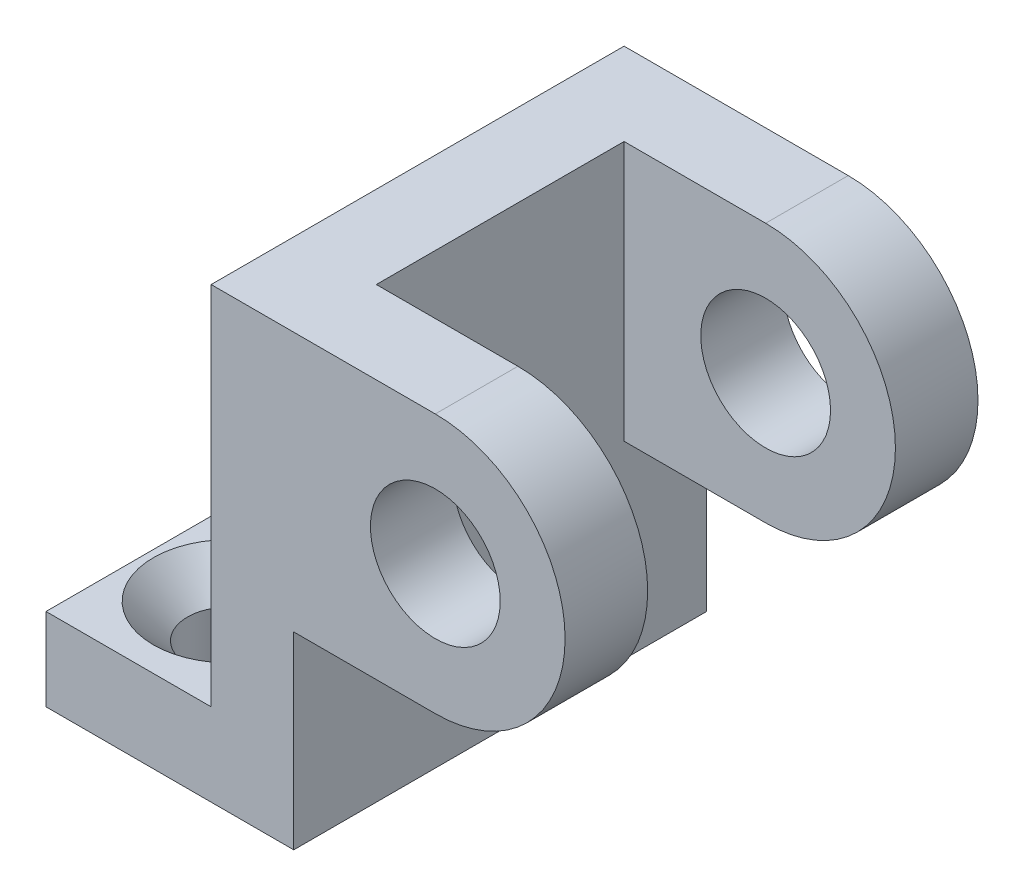
SolidWorks part; units mm, degrees
ref_plane "前视基准面" through (0, 0, 0) normal (0, 0, 1) x (1, 0, 0)
ref_plane "上视基准面" through (0, 0, 0) normal (0, 1, 0) x (1, 0, 0)
ref_plane "右视基准面" through (0, 0, 0) normal (1, 0, 0) x (0, 0, -1)
other "Configuration Table"
sketch "草图1" plane through (0, 0, 0) normal (0, 1, 0) x (1, 0, 0)
  line L1 (7, -17.5) -> (-7, -17.5)
  line L2 (7, -17.5) -> (7, 17.5)
  line L3 (7, 17.5) -> (-7, 17.5)
  line L4 (-7, -17.5) -> (-7, 17.5)
  line L5 (7, -17.5) -> (-7, 17.5) construction
  line L6 (7, 17.5) -> (-7, -17.5) construction
  point P0 (0, 0)
  dimension "D1" = 14
  dimension "D2" = 35
extrude "凸台-拉伸1" add sketch "草图1" along normal blind 7
ref_plane "基准面1" through (0, 7, 0) normal (0, 1, 0) x (1, 0, 0)
sketch "草图4" plane through (0, 7, 0) normal (0, 1, 0) x (1, 0, 0)
  line L0 (0, 0) -> (0, 19.8046) construction
  circle A0 centre (0, 9) radius 0.5
  circle A1 centre (0, -9) radius 0.5
  point P1 (0, 9)
  point P6 (0, -9)
  dimension "D1" = 1
  dimension "D2" = 1
  dimension "D3" = 9
  dimension "D4" = 9
hole_wizard "M6 内六角花形半沉头螺钉的锥形沉头孔1" positions "草图4" profile "草图5" countersink size "M6" standard "GB" end condition through all
sketch "草图5" plane through (0, 7, 9) normal (1, 0, 0) x (0, 0, 1)
  line L0 (0, 0) -> (0, 7)
  line L1 (0, 7) -> (3.5, 7)
  line L2 (3.5, 7) -> (3.5, 2.9)
  line L3 (3.5, 2.9) -> (6.4, 0)
  line L5 (6.4, 0) -> (0, 0)
  line L6 (-3.5, 2.9) -> (-6.4, 0) construction
  line L11 (0, -6.35) -> (0, 107.95) construction
  dimension "通孔孔直径" = 7
  dimension "通孔孔深度" = 7
  dimension "近端锥形沉头孔直径" = 12.8
  dimension "近端锥形沉头孔角度" = 90
sketch "草图6" plane through (0, 0, 0) normal (0, 1, 0) x (1, 0, 0)
  line L1 (7, 17.5) -> (14, 17.5)
  line L2 (7, 17.5) -> (7, -17.5)
  line L3 (7, -17.5) -> (14, -17.5)
  line L4 (14, 17.5) -> (14, -17.5)
  line L5 (7, 17.5) -> (14, -17.5) construction
  line L6 (7, -17.5) -> (14, 17.5) construction
  point P0 (10.5, 0)
  dimension "D1" = 35
  dimension "D2" = 7
  dimension "D3" = 10.5
extrude "凸台-拉伸2" add sketch "草图6" along normal blind 38
ref_plane "基准面2" through (0, 0, 17.5) normal (0, 0, 1) x (1, 0, 0)
sketch "草图7" plane through (0, 0, 17.5) normal (0, 0, 1) x (1, 0, 0)
  line L0 (14, 38) -> (26, 38)
  line L1 (14, 16) -> (26, 16)
  line L2 (14, 38) -> (14, 0) construction
  line L3 (14, 16) -> (14, 38)
  arc A0 (26, 16) -> (26, 38) centre (26, 27) ccw
  circle A1 centre (26, 27) radius 5.5
  dimension "D4" = 11
  dimension "D1" = 12
  dimension "D2" = 12
  dimension "D3" = 22
extrude "凸台-拉伸3" add sketch "草图7" against normal blind 7
mirror "镜向1" about plane through (0, 0, 0) normal (0, 0, 1) of "凸台-拉伸3"
